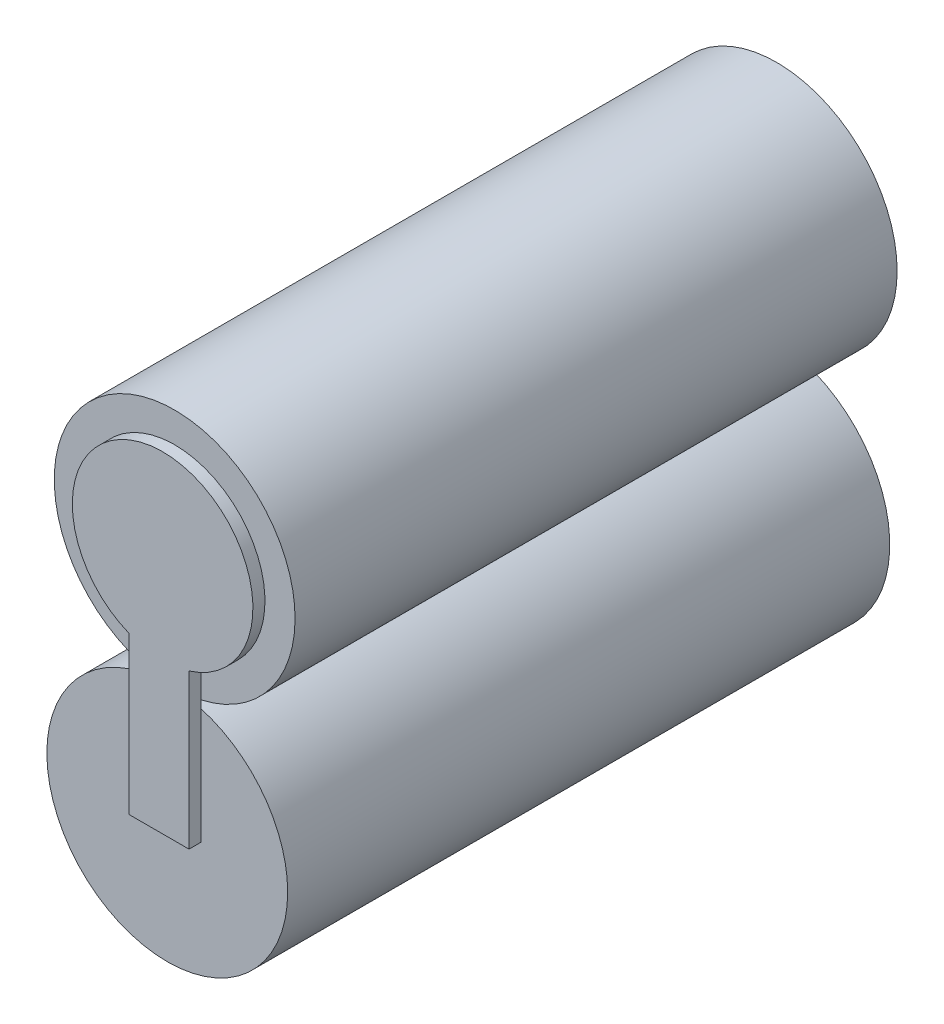
SolidWorks part; units mm, degrees
ref_plane "Plano frontal" through (0, 0, 0) normal (0, 0, 1) x (1, 0, 0)
ref_plane "Plano superior" through (0, 0, 0) normal (0, 1, 0) x (1, 0, 0)
ref_plane "Plano direito" through (0, 0, 0) normal (1, 0, 0) x (0, 0, -1)
sketch "Esboço1" plane through (0, 0, 0) normal (0, 0, 1) x (1, 0, 0)
  line L0 (-67.3089, 529.6968) -> (-67.9227, 509.7062) construction
  circle A0 centre (-67.3089, 529.6968) radius 10
  circle A1 centre (-67.9227, 509.7062) radius 10
  dimension "D1" = 20
extrude "Ressalto-extrusão1" add sketch "Esboço1" along normal blind 50
sketch "Esboço2" plane through (0, 0, 50) normal (0, 0, 1) x (1, 0, 0)
  line L0 (-67.3089, 529.6968) -> (-67.3089, 529.6965) construction
  line L1 (-67.6158, 519.7015) -> (-67.9227, 509.7062) construction
  line L3 (-65.1158, 522.5246) -> (-65.1158, 509.7065)
  line L4 (-65.1158, 509.7065) -> (-70.1158, 509.7065)
  line L5 (-70.1158, 522.7418) -> (-70.1158, 509.7065)
  line L6 (-67.6158, 519.7015) -> (-70.1158, 509.7065) construction
  line L7 (-65.1158, 509.7065) -> (-67.6158, 519.7015) construction
  arc A0 (-65.1158, 522.5246) -> (-70.1158, 522.7418) centre (-67.3089, 529.6968) ccw
  point P3 (-67.6158, 519.7015)
extrude "Ressalto-extrusão2" add sketch "Esboço2" along normal blind 1
sketch "Esboço3" plane through (0, 0, 0) normal (0, 0, -1) x (-1, 0, 0)
  line L0 (67.9227, 509.7062) -> (67.9227, 509.7065) construction
  line L1 (67.6158, 519.7015) -> (67.3089, 529.6968) construction
  line L3 (70.1158, 516.8784) -> (70.1158, 529.6965)
  line L4 (70.1158, 529.6965) -> (65.1158, 529.6965)
  line L5 (65.1158, 516.6612) -> (65.1158, 529.6965)
  line L6 (67.6158, 519.7015) -> (65.1158, 529.6965) construction
  line L7 (70.1158, 529.6965) -> (67.6158, 519.7015) construction
  arc A0 (65.1158, 516.6612) -> (70.1158, 516.8784) centre (67.9227, 509.7062) ccw
  point P3 (67.6158, 519.7015)
extrude "Ressalto-extrusão3" add sketch "Esboço3" along normal blind 1
